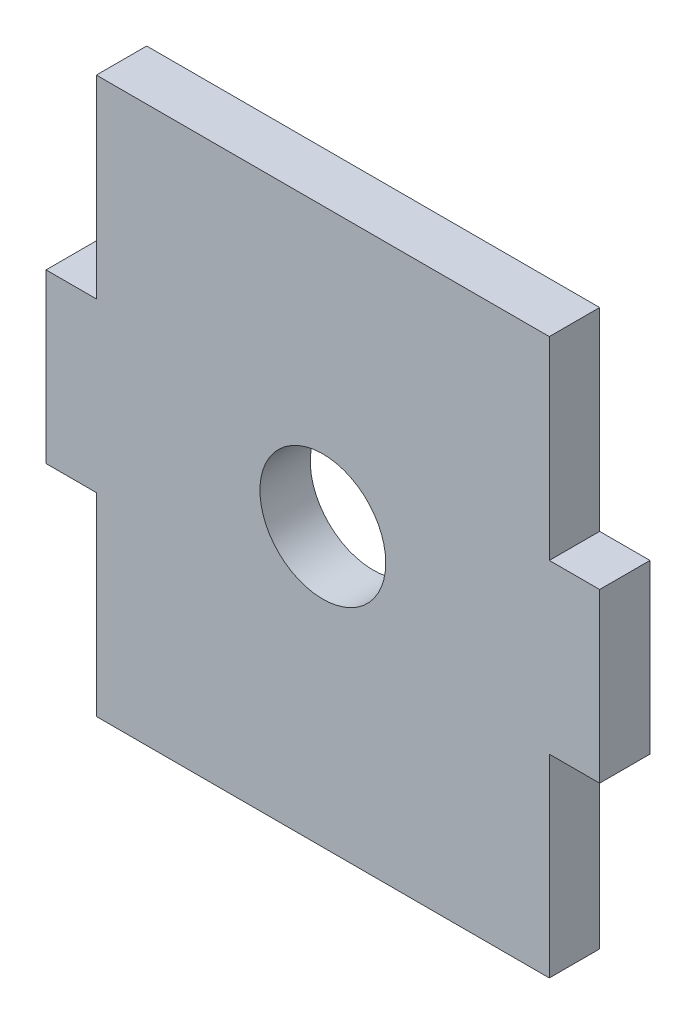
SolidWorks part; units mm, degrees
ref_plane "Alzado" through (0, 0, 0) normal (0, 0, 1) x (1, 0, 0)
ref_plane "Planta" through (0, 0, 0) normal (0, 1, 0) x (1, 0, 0)
ref_plane "Vista lateral" through (0, 0, 0) normal (1, 0, 0) x (0, 0, -1)
sketch "Croquis1" plane through (0, 0, 0) normal (0, 0, 1) x (1, 0, 0)
  line L0 (-13.5, 5) -> (-13.5, 16.5563)
  line L1 (-13.5, -16.5563) -> (13.5, -16.5563)
  line L2 (-13.5, -16.5563) -> (-13.5, -5)
  line L3 (-13.5, 16.5563) -> (13.5, 16.5563)
  line L4 (13.5, -16.5563) -> (13.5, -5)
  line L5 (-13.5, -16.5563) -> (13.5, 16.5563) construction
  line L6 (-13.5, 16.5563) -> (13.5, -16.5563) construction
  line L7 (-16.5, -5) -> (-13.5, -5)
  line L8 (-16.5, -5) -> (-16.5, 5)
  line L9 (-16.5, 5) -> (-13.5, 5)
  line L10 (13.5, 5) -> (13.5, 16.5563)
  line L13 (16.5, -5) -> (13.5, -5)
  line L14 (16.5, -5) -> (16.5, 5)
  line L15 (16.5, 5) -> (13.5, 5)
  circle A0 centre (0, 0) radius 3.75
  point P0 (0, 0)
  point P6 (-13.5, 0)
  point P11 (13.5, 0)
  dimension "D1" = 27
  dimension "D2" = 33.1127
  dimension "D3" = 10
  dimension "D6" = 10
extrude "Saliente-Extruir1" add sketch "Croquis1" along normal blind 3
